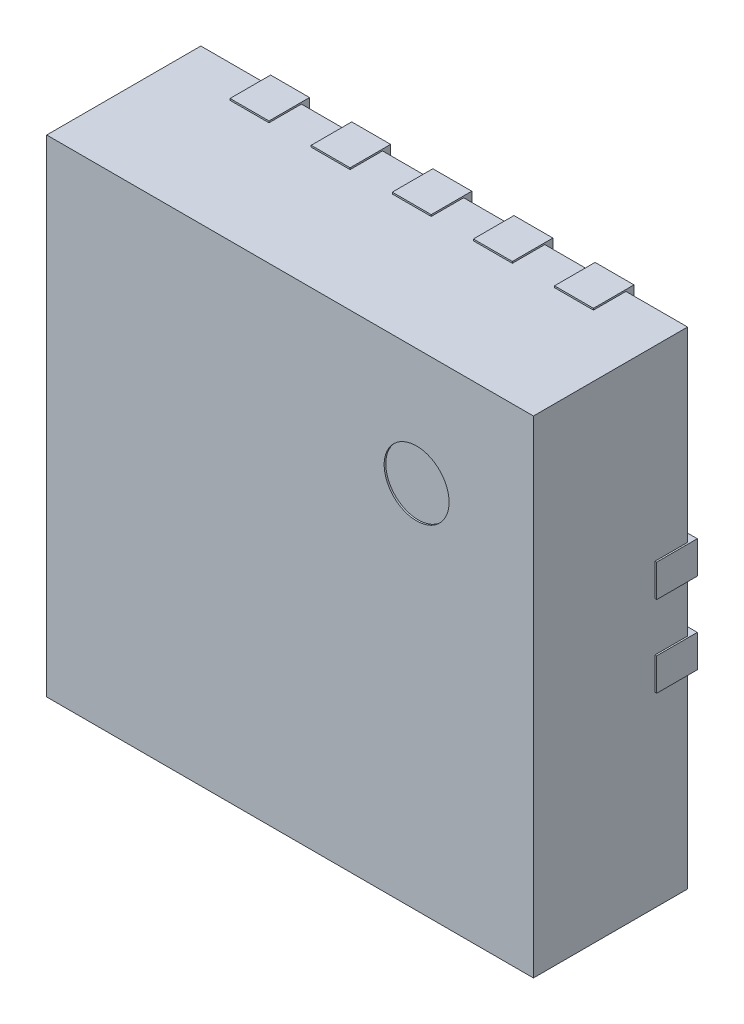
SolidWorks part; units mm, degrees
ref_plane "Front Plane" through (0, 0, 0) normal (0, 0, 1) x (1, 0, 0)
ref_plane "Top Plane" through (0, 0, 0) normal (0, 1, 0) x (1, 0, 0)
ref_plane "Right Plane" through (0, 0, 0) normal (1, 0, 0) x (0, 0, -1)
sketch "Sketch1" plane through (0, 0, 0) normal (0, 0, 1) x (1, 0, 0)
  line L1 (-1.5, 1.5) -> (1.5, 1.5)
  line L2 (-1.5, 1.5) -> (-1.5, -1.5)
  line L3 (-1.5, -1.5) -> (1.5, -1.5)
  line L4 (1.5, 1.5) -> (1.5, -1.5)
  line L5 (-1.5, 1.5) -> (1.5, -1.5) construction
  line L6 (-1.5, -1.5) -> (1.5, 1.5) construction
  point P0 (0, 0)
  dimension "D1" = 3
  dimension "D2" = 3
extrude "Boss-Extrude1" add sketch "Sketch1" along normal blind 0.95 contours L4 L3 L2 L1
sketch "Sketch2" plane through (0, 0, 0.95) normal (0, 0, 1) x (1, 0, 0)
  line L0 (0.78, 0.78) -> (0.78, 1.5) construction
  line L1 (-1.5, 1.5) -> (1.5, 1.5) construction
  line L2 (0.78, 0.78) -> (1.5, 0.78) construction
  line L4 (1.5, 1.5) -> (1.5, -1.5) construction
  circle A0 centre (0.78, 0.78) radius 0.2
  dimension "D1" = 0.4
  dimension "D2" = 0.72
extrude "Cut-Extrude1" cut sketch "Sketch2" against normal blind 0.01
sketch "Sketch3" plane through (0, 0, 0) normal (0, 0, -1) x (-1, 0, 0)
  line L0 (1.2, 0.35) -> (1.51, 0.35)
  line L1 (1.1798, -0.825) -> (-1.1797, -0.825)
  line L2 (1.2, -0.8047) -> (1.2, -0.35)
  line L3 (1.1798, 0.825) -> (-1.1797, 0.825)
  line L4 (-1.2, -0.8047) -> (-1.2, -0.35)
  line L5 (1.2, -0.825) -> (-1.2, 0.825) construction
  line L6 (1.2, 0.825) -> (-1.2, -0.825) construction
  line L7 (1.5, 1.5) -> (1.5, -1.5) construction
  line L8 (1.51, 0.35) -> (1.51, 0.15)
  line L9 (1.51, 0.15) -> (1.2, 0.15)
  line L10 (1.2, 0.15) -> (1.2, -0.15)
  line L11 (1.2, -0.15) -> (1.51, -0.15)
  line L12 (1.51, -0.15) -> (1.51, -0.35)
  line L13 (1.51, -0.35) -> (1.2, -0.35)
  line L14 (1.2, 0.35) -> (1.2, 0.8048)
  line L15 (-1.2, 0.35) -> (-1.51, 0.35)
  line L16 (-1.5, 1.5) -> (-1.5, -1.5) construction
  line L17 (-1.51, 0.35) -> (-1.51, 0.15)
  line L18 (-1.51, 0.15) -> (-1.2, 0.15)
  line L19 (-1.2, 0.15) -> (-1.2, -0.15)
  line L20 (-1.2, -0.15) -> (-1.51, -0.15)
  line L21 (-1.51, -0.15) -> (-1.51, -0.35)
  line L22 (-1.51, -0.35) -> (-1.2, -0.35)
  line L23 (-1.2, 0.35) -> (-1.2, 0.8048)
  line L24 (-1, 0.825) -> (-1.2, 0.625)
  arc A0 (-1.1797, -0.825) -> (-1.2, -0.8047) centre (-1.1797, -0.8047) cw
  arc A1 (-1.1797, 0.825) -> (-1.2, 0.8048) centre (-1.1797, 0.8048) ccw
  arc A2 (1.2, 0.8048) -> (1.1798, 0.825) centre (1.1798, 0.8048) ccw
  arc A3 (1.2, -0.8047) -> (1.1798, -0.825) centre (1.1798, -0.8047) cw
  point P0 (0, 0)
  point P28 (1.2, 0)
  point P30 (1.51, -0.25)
  point P31 (1.51, 0.25)
  point P41 (-1.2, 0)
  line M2 (-1.5, 1.5) -> (-1.5, -1.5)
  line M4 (1.5, -1.5) -> (1.5, 1.5)
  dimension "D3" = 0.0203
  dimension "D1" = 2.4
  dimension "D2" = 1.65
  dimension "D4" = 0.2
  dimension "D5" = 0.5
  dimension "D7" = 0.2
  dimension "D9" = 45
  dimension "D10" = 0.2
  dimension "D11" = 0.01
  dimension "D12" = 0.01
extrude "Boss-Extrude2" add sketch "Sketch3" along normal blind 0.05 and the other way blind 0.2 contours A3 L2 L13 L11 L10 L9 L0 L14 A2 L3 L24 L23 L15 L18 L19 L20 L22 L4 A0 L1 M4 M2 | L9 L8 L0 M4 | L13 L12 L11 M4 | L21 L22 L20 M2 | L17 L18 L15 M2
sketch "Sketch6" plane through (0, 0, 0) normal (0, 0, -1) x (-1, 0, 0)
  line L0 (-1.12, 1.51) -> (-0.88, 1.51)
  line L1 (-0.88, 1.51) -> (-0.88, 1.5)
  line L2 (1.5, 1.5) -> (-1.5, 1.5) construction
  line L3 (-0.88, 1.5) -> (-0.88, 1.22)
  line L4 (-1.12, 1.51) -> (-1.12, 1.5)
  line L5 (-1.12, 1.5) -> (-1.12, 1.22)
  arc A0 (-1.12, 1.22) -> (-0.88, 1.22) centre (-1, 1.22) ccw
  point P9 (-1, 1.1)
  dimension "D1" = 0.01
  dimension "D2" = 0.24
  dimension "D3" = 0.4
  dimension "D4" = 1
extrude "Boss-Extrude4" add sketch "Sketch6" along normal blind 0.05 and the other way blind 0.2
pattern_linear "LPattern2" count 5 spacing 0.5 along (-1, 0, 0) of "Boss-Extrude4"
mirror "Mirror2" about plane through (0, 0, 0) normal (0, 1, 0) of "LPattern2", "Boss-Extrude4"
equation "\"E\" = 3"
equation "\"D\" = 3"
equation "\"H\"= \"A\" + \"A1\""
equation "\"D1@Boss-Extrude1\"=\"H\""
equation "\"D2@Sketch1\"=\"E\""
equation "\"D1@Sketch1\"=\"D\""
equation "\"D2\" = 2.4"
equation "\"E2\" = 1.65"
equation "\"L\"= 0.4"
equation "\"b\"= 0.24"
equation "\"e_\"= 0.5"
equation "\"A3\"= 0.2"
equation "\"K\"= 0.2"
equation "\"A1\"= 0.05"
equation "\"D1@Sketch3\"=\"D2\""
equation "\"D2@Sketch3\"=\"E2\""
equation "\"GND_R\"= ( \"D2\" + \"E2\" ) / 2 * 0.01"
equation "\"D3@Sketch3\"=\"GND_R\""
equation "\"D1@Boss-Extrude2\"=\"A1\""
equation "\"Px\"= 5"
equation "\"Py\"= 2"
equation "\"P\"= 2 * \"Px\" + 2 * \"Py\""
equation "\"D2@Sketch6\"=\"b\""
equation "\"D3@Sketch6\"=\"L\""
equation "\"D4@Sketch6\"=(\"Px\"/2-1)*\"e_\"+\"e_\"/2"
equation "\"D1@Boss-Extrude4\"=\"A1\""
equation "\"D2@Boss-Extrude4\"=\"A3\""
equation "\"D3@LPattern2\"=\"e_\""
equation "\"D1@LPattern2\"=\"Px\""
equation "\"A\"= 0.9"
equation "\"D2@Sketch2\"=\"D1@Sketch2\"*1.8"
equation "\"e_y\"= 1.5"
equation "\"D7@Sketch3\"=\"D4@Sketch3\""
equation "\"D2@Boss-Extrude2\"=\"A3\""
equation "\"D12@Sketch3\"=\"D11@Sketch3\""
